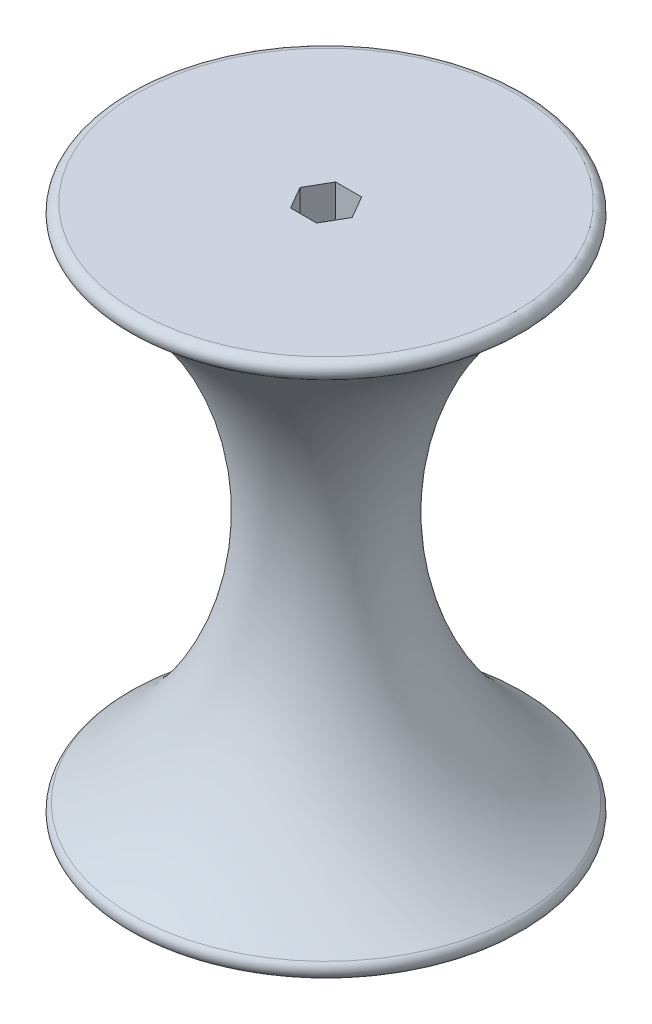
SolidWorks part; units mm, degrees
ref_plane "Front Plane" through (0, 0, 0) normal (0, 0, 1) x (1, 0, 0)
ref_plane "Top Plane" through (0, 0, 0) normal (0, 1, 0) x (1, 0, 0)
ref_plane "Right Plane" through (0, 0, 0) normal (1, 0, 0) x (0, 0, -1)
sketch "Sketch1" plane through (0, 0, 0) normal (0, 0, 1) x (1, 0, 0)
  line L1 (0, -76.2) -> (53.7699, -76.2)
  line L2 (0, -76.2) -> (0, 76.2)
  line L3 (0, 76.2) -> (53.7699, 76.2)
  arc A0 (55.2749, 71.6139) -> (55.2749, -71.6139) centre (107.95, 0) ccw
  arc A1 (55.2749, -71.6139) -> (53.7699, -76.2) centre (53.7699, -73.66) cw
  arc A2 (53.7699, 76.2) -> (55.2749, 71.6139) centre (53.7699, 73.66) cw
  point P10 (19.05, 0)
  point P12 (0, 0)
  dimension "D2" = 88.9
  dimension "D4" = 19.05
  dimension "D3" = 2.54
  dimension "D5" = 152.4
ref_axis "Axis1" through (0, -76.2, 0) along (0, 1, 0)
revolve "Revolve1" add sketch "Sketch1" angle 360 about axis through (0, -76.2, 0) along (0, 1, 0)
sketch "Sketch3" plane through (0, 76.2, 0) normal (0, 1, 0) x (1, 0, 0)
  line L0 (7.4057, 0) -> (3.7028, -6.4135)
  line L1 (3.7028, -6.4135) -> (-3.7028, -6.4135)
  line L2 (-3.7028, -6.4135) -> (-7.4057, 0)
  line L3 (-7.4057, 0) -> (-3.7028, 6.4135)
  line L4 (-3.7028, 6.4135) -> (3.7028, 6.4135)
  line L5 (3.7028, 6.4135) -> (7.4057, 0)
  line L6 (7.4057, 0) -> (-7.4057, 0) construction
  circle A1 centre (0, 0) radius 53.7699
  circle A3 centre (0, 0) radius 53.7699 construction
  point P5 (0, 0)
  dimension "D2" = 12.827
  dimension "D3" = 12.827
  dimension "D1" = 0
extrude "Cut-Extrude1" cut sketch "Sketch3" against normal through all
sketch "Sketch4" plane through (0, 76.2, 0) normal (0, 1, 0) x (1, 0, 0)
  line L0 (3.7028, 6.4135) -> (-3.7028, 6.4135) construction
  line L1 (3.7028, 6.4135) -> (-3.7028, 6.4135) construction
  circle A0 centre (0, 0) radius 56.3099 construction
  circle A1 centre (0, 0) radius 56.3099 construction
ref_plane "Plane1" through (0, 0, -56.3035) normal (0, 0, 1) x (1, 0, 0)
